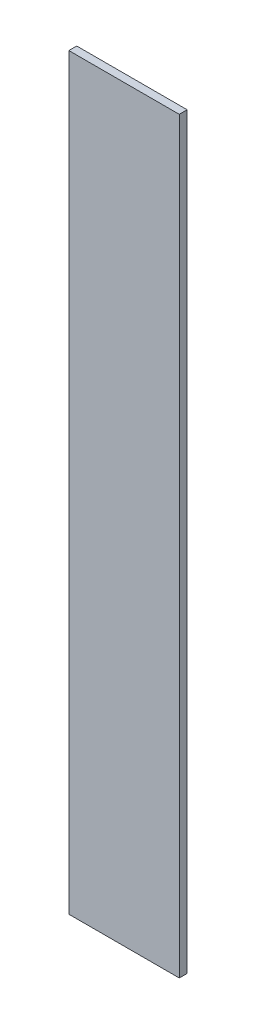
SolidWorks part; units mm, degrees
ref_plane "Front Plane" through (0, 0, 0) normal (1, 0, 0) x (0, 1, 0)
ref_plane "Top Plane" through (0, 0, 0) normal (0, 0, 1) x (0, 1, 0)
ref_plane "Right Plane" through (0, 0, 0) normal (0, 1, 0) x (-1, 0, 0)
sketch "Sketch2" plane through (0, 0, 0) normal (0, 0, 1) x (0, 1, 0)
  line L1 (0, 0) -> (602.234, 0)
  line L2 (0, 0) -> (0, 88.9)
  line L3 (0, 88.9) -> (602.234, 88.9)
  line L4 (602.234, 0) -> (602.234, 88.9)
  dimension "D1" = 88.9
  dimension "D2" = 602.234
extrude "Boss-Extrude1" add sketch "Sketch2" along normal blind 6.35
